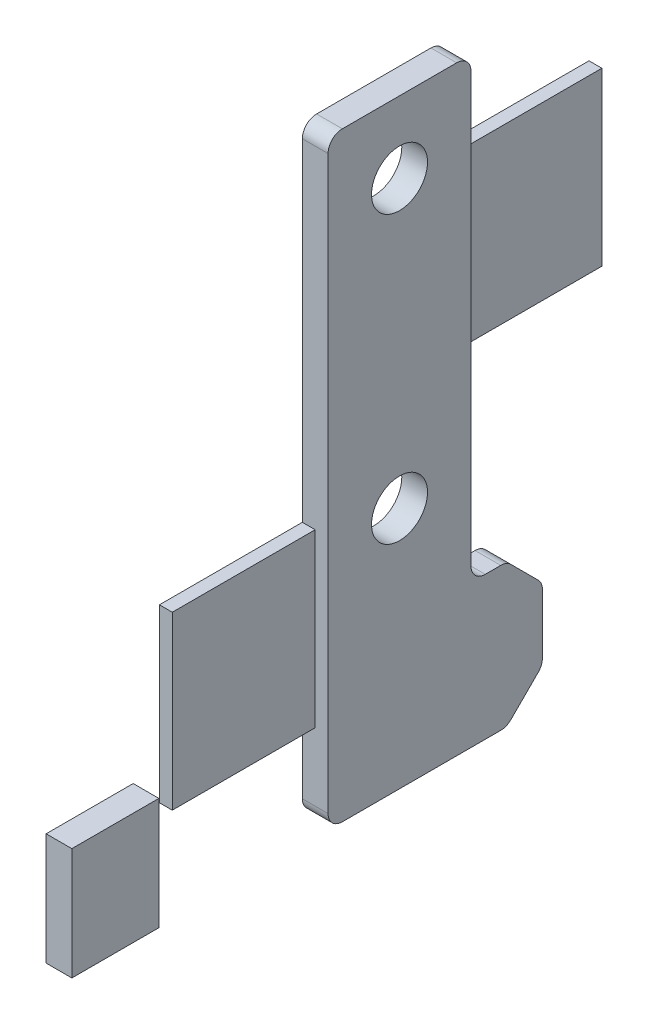
SolidWorks part; units mm, degrees
material "5052-H32"
ref_plane "Front Plane" through (0, 0, 0) normal (0, 0, 1) x (1, 0, 0)
ref_plane "Top Plane" through (0, 0, 0) normal (0, 1, 0) x (1, 0, 0)
ref_plane "Right Plane" through (0, 0, 0) normal (1, 0, 0) x (0, 0, -1)
sketch "Sketch1" plane through (0, 0, -8.688) normal (1, 0, 0) x (0, 0, -1)
  line L8 (0, 0) -> (0, 53.34)
  line L9 (0, 53.34) -> (12.7, 53.34)
  line L10 (12.7, 53.34) -> (12.7, 12.7)
  line L11 (12.7, 12.7) -> (19.05, 12.7)
  line L12 (19.05, 12.7) -> (19.05, 0)
  line L13 (19.05, 0) -> (0, 0)
  circle A0 centre (6.35, 46.99) radius 2.4892
  circle A1 centre (6.35, 21.59) radius 2.4892
  point P12 (6.35, 53.34)
  dimension "D4" = 25.4
  dimension "D5" = 4.9784
  dimension "D1" = 12.7
  dimension "D2" = 19.05
  dimension "D3" = 53.34
  dimension "D6" = 6.35
  dimension "D7" = 12.7
extrude "Boss-Extrude1" add sketch "Sketch1" along normal blind 2.286
chamfer "Chamfer1" distance 3.175 angle 45 2 edges at (1.143, 0, -27.738) (1.143, 12.7, -27.738)
fillet "Fillet2" radius 1.27 8 edges at (1.143, 53.34, -8.688) (1.143, 53.34, -21.388) (1.143, 12.7, -21.388) (1.143, 0, -8.688) (1.143, 3.175, -27.738) (1.143, 0, -24.563) (1.143, 9.525, -27.738) (1.143, 12.7, -24.563)
sketch "Sketch3" plane through (0, 0, 0) normal (-1, 0, 0) x (0, 0, 1)
  line L1 (14.0804, 0) -> (6.3454, 0)
  line L2 (14.0804, 0) -> (14.0804, 9.9572)
  line L3 (14.0804, 9.9572) -> (6.3454, 9.9572)
  line L4 (6.3454, 0) -> (6.3454, 9.9572)
extrude "Boss-Extrude2" add sketch "Sketch3" against normal up to surface (2.286 mm away) separate body up to face at (2.286, 18.0975, -20.6702)
sketch "Sketch5" plane through (0, 0, 0) normal (-1, 0, 0) x (0, 0, 1)
  line L0 (-8.688, 22.5464) -> (-8.688, 7.3064)
  line L1 (-8.688, 22.5464) -> (4.012, 22.5464)
  line L2 (-8.688, 7.3064) -> (4.012, 7.3064)
  line L3 (4.012, 22.5464) -> (4.012, 7.3064)
  line L4 (-8.688, 52.07) -> (-8.688, 1.27) construction
  line L5 (-21.388, 45.3271) -> (-21.388, 30.0871)
  line L6 (-21.388, 45.3271) -> (-34.1657, 45.3271)
  line L7 (-21.388, 30.0871) -> (-34.1657, 30.0871)
  line L8 (-34.1657, 45.3271) -> (-34.1657, 30.0871)
  line L9 (-21.388, 13.97) -> (-21.388, 52.07) construction
  dimension "D1" = 15.24
  dimension "D3" = 15.24
extrude "Boss-Extrude3" add sketch "Sketch5" against normal blind 1.143
